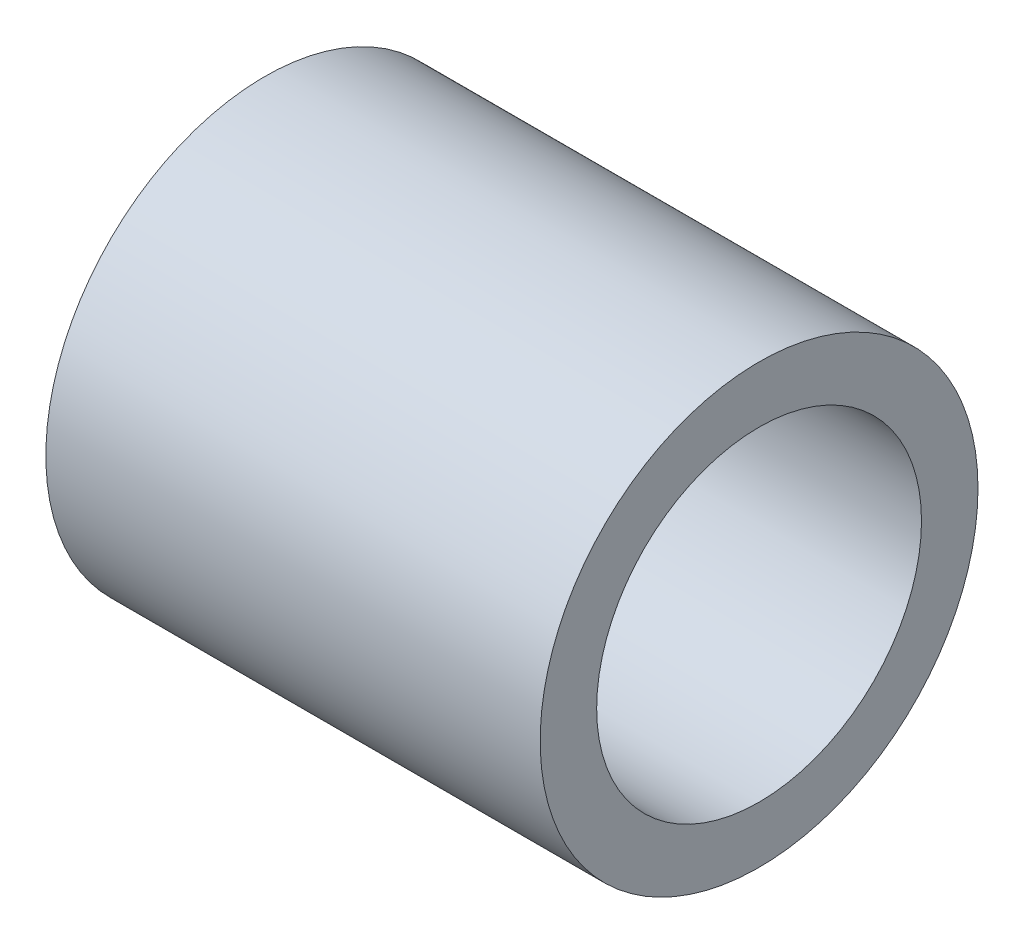
SolidWorks part; units mm, degrees
material "Brass"
ref_plane "Front Plane" through (0, 0, 0) normal (0, 0, 1) x (1, 0, 0)
ref_plane "Top Plane" through (0, 0, 0) normal (0, 1, 0) x (1, 0, 0)
ref_plane "Right Plane" through (0, 0, 0) normal (1, 0, 0) x (0, 0, -1)
sketch "Sketch2" plane through (0, 0, 0) normal (1, 0, 0) x (0, 0, -1)
  circle A0 centre (0, 0) radius 7.3025
  circle A1 centre (0, 0) radius 9.8425
  dimension "D1" = 14.605
  dimension "D2" = 19.685
extrude "Boss-Extrude1" add sketch "Sketch2" along normal blind 22.225
